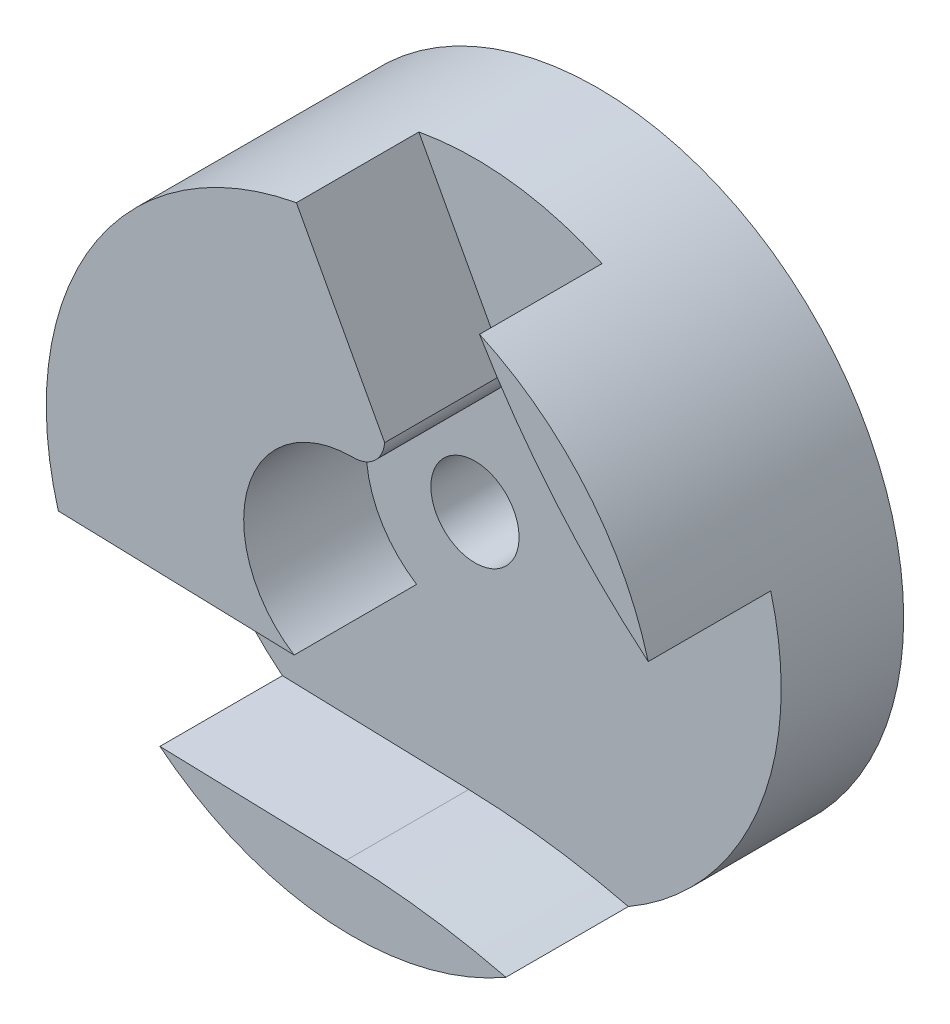
SolidWorks part; units mm, degrees
ref_plane "Alzado" through (0, 0, 0) normal (0, 0, 1) x (1, 0, 0)
ref_plane "Planta" through (0, 0, 0) normal (0, 1, 0) x (1, 0, 0)
ref_plane "Vista lateral" through (0, 0, 0) normal (1, 0, 0) x (0, 0, -1)
sketch "Croquis1" plane through (0, 0, 0) normal (0, 0, 1) x (1, 0, 0)
  line L0 (-0.4248, 0) -> (4.4052, 0) construction
  line L1 (-0.4248, 0) -> (-13.4152, 7.5) construction
  line L2 (15.4129, -8.051) -> (15.4248, -8.0571)
  line L3 (-2.6531, 14.8336) -> (1.6562, 6.8432)
  line L4 (1.295, -4.5134) -> (7.0786, -2.3097)
  line L5 (-10.4658, -11.1436) -> (-0.7158, -11.4264)
  line L6 (15.4248, -8.0571) -> (15.4129, -8.051)
  line L7 (6.4239, -2.8266) -> (2.8915, -4.1726)
  line L8 (-2.1846, -5.0311) -> (-14.6798, -4.6687)
  line L9 (-9.8594, -11.6614) -> (-0.7303, -11.9262)
  line L10 (-3.0932, 14.5962) -> (1.1507, 6.7273)
  line L11 (-3.2827, -4.499) -> (-14.6653, -4.1689)
  line L12 (-10.4803, -11.6434) -> (-0.7303, -11.9262) construction
  line L13 (-0.5576, -4.5781) -> (-14.6653, -4.1689) construction
  line L14 (-0.5721, -5.0779) -> (-14.6798, -4.6687) construction
  circle A0 centre (-0.4248, 0) radius 2.159
  circle A1 centre (-0.4248, 0) radius 4.83
  circle A2 centre (-0.4248, 0) radius 15
  arc A3 (12.5264, -7.5674) -> (11.8318, -8.5008) centre (13.7376, -9.1939) ccw
  arc A4 (5.0353, 13.9709) -> (14.2538, 3.0885) centre (38.2023, 32.7209) ccw
  arc A5 (-0.3875, 4.8299) -> (1.6562, 6.8432) centre (-0.3718, 6.8578) ccw
  arc A6 (-0.3875, 4.8299) -> (1.295, -4.5134) centre (-0.4248, 0) ccw
  arc A7 (9.7559, -5.4294) -> (7.0786, -2.3097) centre (9.8488, -2.641) ccw
  arc A8 (9.7559, -5.4294) -> (11.8318, -8.5008) centre (9.6797, -7.7181) ccw
  arc A9 (7.6889, -12.6161) -> (-0.7158, -11.4264) centre (-1.8203, -49.5104) ccw
  arc A10 (9.7642, -5.1796) -> (10.7264, -10.0324) centre (9.6797, -7.7181) ccw
  arc A11 (9.7642, -5.1796) -> (7.4618, -1.7728) centre (9.8488, -2.641) ccw
  arc A12 (6.4239, -2.8266) -> (7.4618, -1.7728) centre (5.7908, -1.1652) ccw
  arc A14 (5.7989, 13.6479) -> (14.0607, 3.8948) centre (38.2023, 32.7209) ccw
  arc A15 (7.0905, -12.9815) -> (-0.7303, -11.9262) centre (-1.8203, -49.5104) ccw
  arc A16 (-0.3836, 5.3298) -> (1.1507, 6.7273) centre (-0.3718, 6.8578) ccw
  arc A17 (-0.3836, 5.3298) -> (3.4011, -3.7109) centre (-0.4248, 0) ccw
  circle A18 centre (-0.4248, 0) radius 5.33 construction
  arc A19 (7.5641, -13.1003) -> (-0.7303, -11.9262) centre (-1.8203, -49.5104) ccw construction
  arc A20 (5.4706, 14.217) -> (14.568, 3.4774) centre (38.2023, 32.7209) ccw construction
  dimension "D1" = 150
  dimension "D2" = 15
  dimension "D3" = 0.5
  dimension "D4" = 0.5
sketch "Croquis2" plane through (0, 0, 0) normal (0, 0, 1) x (1, 0, 0)
  circle A0 centre (-0.4248, 0) radius 15
extrude "Saliente-Extruir1" add sketch "Croquis2" along normal blind 6
sketch "Croquis3" plane through (0, 0, 0) normal (0, 0, -1) x (-1, 0, 0)
  circle A0 centre (0.4248, 0) radius 2.159 construction
  circle A1 centre (0.4248, 0) radius 2.159
extrude "Cortar-Extruir1" cut sketch "Croquis3" against normal blind 6
sketch "Croquis5" plane through (0, 0, 6) normal (0, 0, 1) x (1, 0, 0)
  line L0 (-3.0932, 14.5962) -> (1.1507, 6.7273) construction
  line L1 (-3.174, 14.7459) -> (1.1507, 6.7273)
  line L2 (-3.2827, -4.499) -> (-14.6653, -4.1689) construction
  line L3 (-3.2827, -4.499) -> (-14.8353, -4.164)
  line L4 (-9.8594, -11.6614) -> (-0.7303, -11.9262) construction
  line L5 (-9.8594, -11.6614) -> (-0.7303, -11.9262)
  arc A0 (-0.3836, 5.3298) -> (3.4011, -3.7109) centre (-0.4248, 0) ccw construction
  arc A1 (-0.3836, 5.3298) -> (1.1507, 6.7273) centre (-0.3718, 6.8578) ccw construction
  arc A2 (-0.3836, 5.3298) -> (-3.2827, -4.499) centre (-0.4248, 0) ccw
  arc A3 (-0.3836, 5.3298) -> (1.1507, 6.7273) centre (-0.3718, 6.8578) ccw
  circle A4 centre (-0.4248, 0) radius 15 construction
  circle A5 centre (-0.4248, 0) radius 15
  arc A6 (7.0905, -12.9815) -> (-0.7303, -11.9262) centre (-1.8203, -49.5104) ccw construction
  arc A7 (7.0905, -12.9815) -> (-0.7303, -11.9262) centre (-1.8203, -49.5104) ccw
  arc A8 (5.7989, 13.6479) -> (14.0607, 3.8948) centre (38.2023, 32.7209) ccw construction
  arc A9 (5.7989, 13.6479) -> (14.0607, 3.8948) centre (38.2023, 32.7209) ccw
  circle M3 centre (-0.4248, 0) radius 15
extrude "Saliente-Extruir2" add sketch "Croquis5" along normal blind 6 contours A2 A3 L1 L3 M3 | A9 M3 | A7 L5 M3
